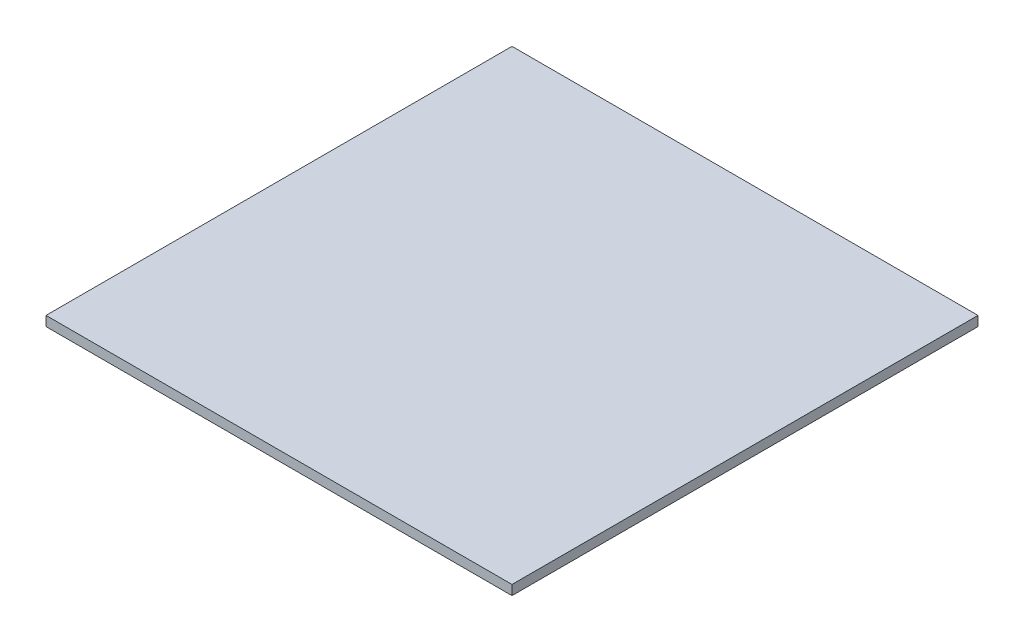
SolidWorks part; units mm, degrees
ref_plane "Front Plane" through (0, 0, 0) normal (0, 0, 1) x (1, 0, 0)
ref_plane "Top Plane" through (0, 0, 0) normal (0, 1, 0) x (1, 0, 0)
ref_plane "Right Plane" through (0, 0, 0) normal (1, 0, 0) x (0, 0, -1)
sketch "Sketch1" plane through (0, 0, 0) normal (0, 1, 0) x (1, 0, 0)
  line L1 (0, 0) -> (240, 0)
  line L2 (0, 0) -> (0, -240)
  line L3 (0, -240) -> (240, -240)
  line L4 (240, 0) -> (240, -240)
  dimension "D1" = 240
extrude "Boss-Extrude1" add sketch "Sketch1" along normal blind 5
